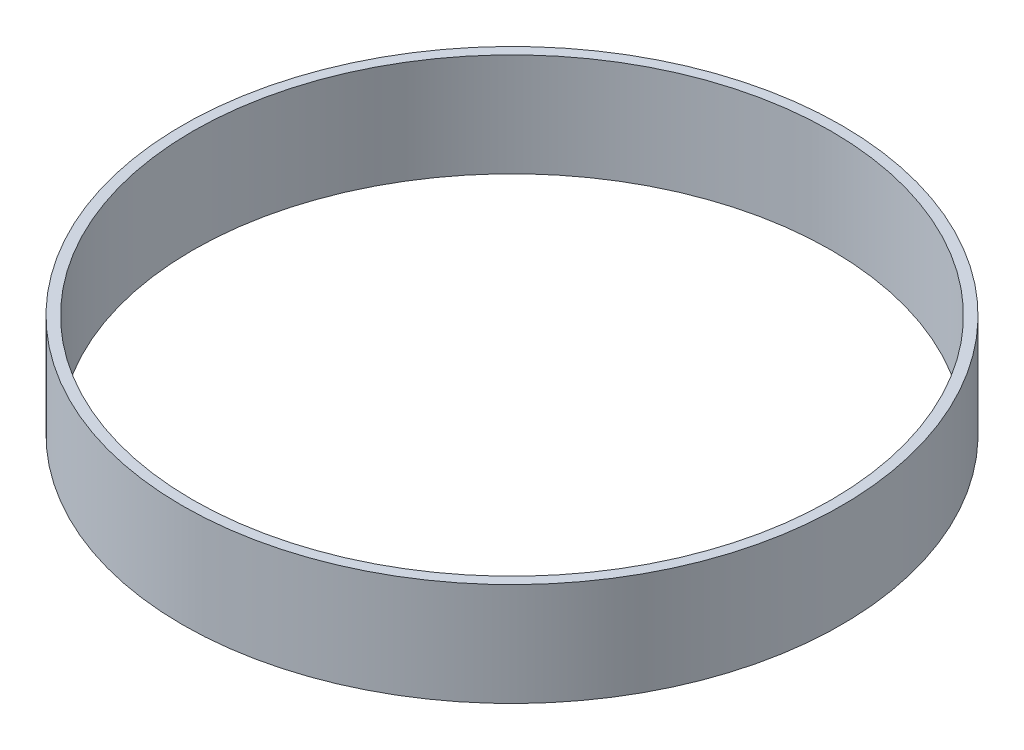
SolidWorks part; units mm, degrees
ref_plane "Front Plane" through (0, 0, 0) normal (0, 0, 1) x (1, 0, 0)
ref_plane "Top Plane" through (0, 0, 0) normal (0, 1, 0) x (1, 0, 0)
ref_plane "Right Plane" through (0, 0, 0) normal (1, 0, 0) x (0, 0, -1)
sketch "Sketch1" plane through (0, 0, 0) normal (0, 1, 0) x (1, 0, 0)
  circle A0 centre (0, 0) radius 160000
  circle A2 centre (0, 0) radius 155000
extrude "Boss-Extrude2" add sketch "Sketch1" along normal blind 50000 separate body
